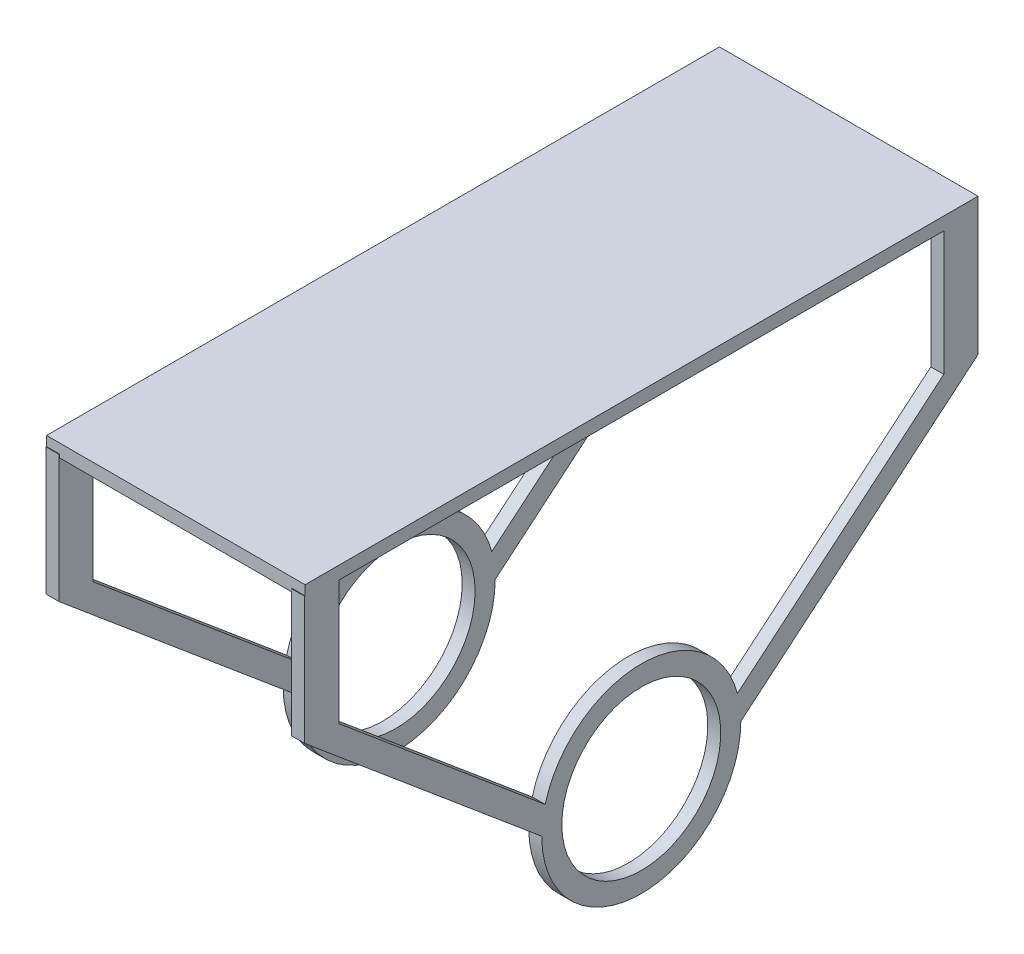
SolidWorks part; units mm, degrees
ref_plane "Front Plane" through (0, 0, 0) normal (0, 0, 1) x (1, 0, 0)
ref_plane "Top Plane" through (0, 0, 0) normal (0, 1, 0) x (1, 0, 0)
ref_plane "Right Plane" through (0, 0, 0) normal (1, 0, 0) x (0, 0, -1)
sketch "Sketch1" plane through (0, 0, 0) normal (1, 0, 0) x (0, 0, -1)
  line L0 (-175.9687, 0) -> (175.9687, 0) construction
  line L1 (0, -79.6814) -> (0, 79.6814) construction
  circle A0 centre (0, 0) radius 77.0031
  circle A1 centre (0, 0) radius 61.4685
  point P4 (0, 0)
  point P8 (0, 0)
extrude "Boss-Extrude1" add sketch "Sketch1" along normal blind 10
sketch "Sketch2" plane through (0, 0, 0) normal (1, 0, 0) x (0, 0, -1)
  line L0 (-74.3604, 20) -> (-233.9572, 153.9176)
  line L1 (-296.833, 20) -> (148.1121, 20) construction
  line L2 (-77.0031, 0) -> (250, 0) construction
  line L4 (-77.0031, 0) -> (-74.1553, 0) construction
  line L9 (-77.0031, 0) -> (-260.435, 153.9176)
  line L10 (-260.435, 153.9176) -> (-233.9572, 153.9176)
  circle A0 centre (0, 0) radius 77.0031 construction
  arc A1 (-77.0031, 0) -> (-74.3604, 20) centre (0, 0) cw
  point P6 (-74.3604, 20)
  point P11 (0, 0)
extrude "Boss-Extrude2" add sketch "Sketch2" along normal blind 10
sketch "Sketch3" plane through (0, 0, 0) normal (1, 0, 0) x (0, 0, -1)
  line L0 (-260.435, 153.9176) -> (-260.435, 252.5329)
  line L1 (-233.9572, 153.9176) -> (-233.9572, 252.5329)
  line L2 (-260.435, 153.9176) -> (-233.9572, 153.9176)
  line L3 (-260.435, 252.5329) -> (-233.9572, 252.5329)
extrude "Boss-Extrude3" add sketch "Sketch3" along normal blind 10
mirror "Mirror2" about plane through (0, 0, 0) normal (0, 0, 1) of "Boss-Extrude3", "Boss-Extrude2"
ref_plane "Plane4" through (200, 0, 0) normal (-1, 0, 0) x (0, 0, 1)
sketch "Sketch5" plane through (200, 0, 0) normal (-1, 0, 0) x (0, 0, 1)
  circle A0 centre (0, 0) radius 61.4685
  circle A1 centre (0, 0) radius 77.0031
extrude "Boss-Extrude4" add sketch "Sketch5" along normal blind 10 separate body
sketch "Sketch7" plane through (200, 0, 0) normal (-1, 0, 0) x (0, 0, 1)
  line L0 (-74.3604, 20) -> (-233.9572, 153.9176)
  line L1 (-77.0031, 0) -> (-260.435, 153.9176)
  line L4 (-260.435, 153.9176) -> (-233.9572, 153.9176)
  arc A0 (-74.3604, 20) -> (-77.0031, 0) centre (0, 0) ccw
extrude "Boss-Extrude5" add sketch "Sketch7" along normal blind 10
sketch "Sketch8" plane through (200, 0, 0) normal (-1, 0, 0) x (0, 0, 1)
  line L0 (-233.9572, 153.9176) -> (-233.9572, 252.5329)
  line L1 (-260.435, 153.9176) -> (-260.435, 252.5329)
  line L2 (-233.9572, 153.9176) -> (-260.435, 153.9176)
  line L3 (-233.9572, 252.5329) -> (-260.435, 252.5329)
extrude "Boss-Extrude6" add sketch "Sketch8" along normal blind 10
mirror "Mirror5" about plane through (0, 0, 0) normal (0, 0, 1) of "Boss-Extrude5"
mirror "Mirror6" about plane through (0, 0, 0) normal (0, 0, 1) of "Boss-Extrude6"
ref_plane "Plane5" through (0, 250, 0) normal (0, 1, 0) x (1, 0, 0)
sketch "Sketch9" plane through (0, 250, 0) normal (0, 1, 0) x (1, 0, 0)
  line L0 (200, 181.2448) -> (200, -181.2448) construction
  line L1 (0, 260.435) -> (200, 260.435)
  line L2 (0, 260.435) -> (0, -260.0188)
  line L3 (0, -260.0188) -> (200, -260.0188)
  line L4 (200, 260.435) -> (200, -260.0188)
extrude "Boss-Extrude7" add sketch "Sketch9" along normal blind 10
